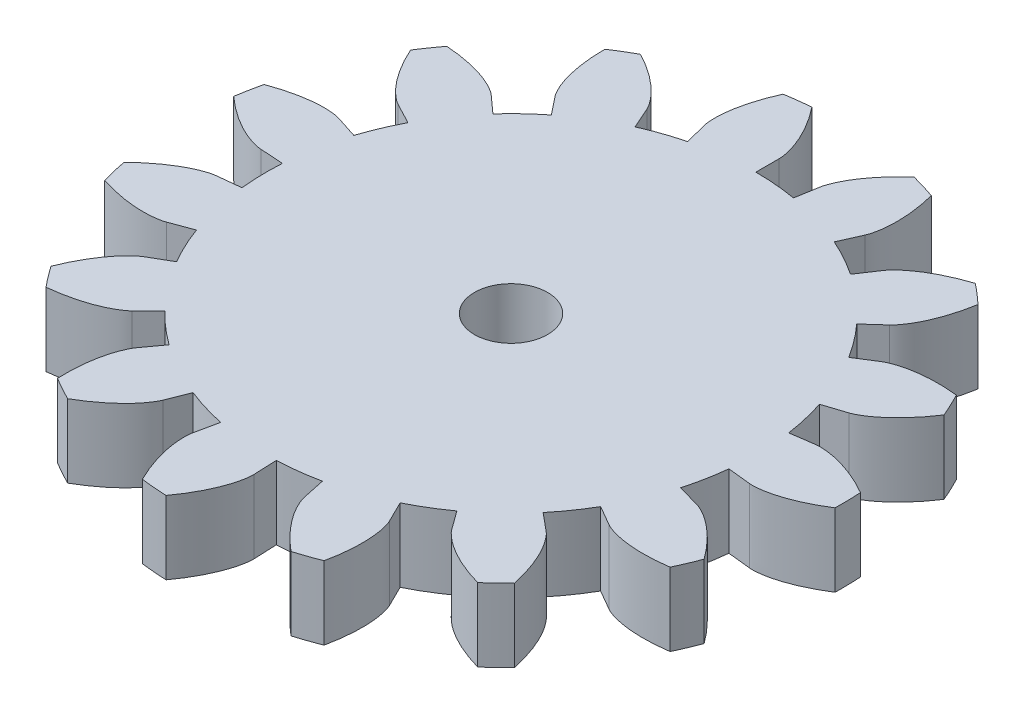
SolidWorks part; units mm, degrees
ref_plane "Front Plane" through (0, 0, 0) normal (0, 0, 1) x (1, 0, 0)
ref_plane "Top Plane" through (0, 0, 0) normal (0, 1, 0) x (1, 0, 0)
ref_plane "Right Plane" through (0, 0, 0) normal (1, 0, 0) x (0, 0, -1)
sketch "Reference attributes" plane through (0, 0, 0) normal (0, 1, 0) x (1, 0, 0)
  line L0 (0, 0) -> (15, 0) construction
  line L1 (0, -10) -> (1.56, -10) construction
  line L2 (0, 0) -> (14.4889, 3.8823) construction
  line L3 (0, 0) -> (14.0954, 5.1303) construction
  dimension "Teeth" = 15
  dimension "Module" = 1.56
  dimension "D2" = 10
  dimension "Helix Angle" = 15
  dimension "Pressure angle" = 20
sketch "Gear billet" plane through (0, 0, 0) normal (0, 1, 0) x (1, 0, 0)
  circle A0 centre (0, 0) radius 13.5525
  dimension "OuterDi" = 27.105
extrude "Gear billet Extrude" add sketch "Gear billet" along normal blind 3
ref_plane "Opposite gear face" through (0, 3, 0) normal (0, 1, 0) x (1, 0, 0)
ref_point "Twist centre point top"
ref_point "Twist centre point bottom"
ref_axis "Axis" through (0, 3, 0) along (0, -1, 0)
sketch "Involute Profile" plane through (0, 3, 0) normal (0, 1, 0) x (1, 0, 0)
  line L0 (0, 0) -> (0, 10.9944) construction
  line L1 (0, 0) -> (1.849, 10.8378) construction
  circle A0 centre (0, 0) radius 11.9925
  circle A4 centre (0, 0) radius 10.9944 construction
  spline S0 degree 4 poles (0, 10.9944) (0, 11.0283) (-0.0045, 11.1233) (-0.0311, 11.3029) (-0.0996, 11.5898) (-0.2249, 11.9512) (-0.4271, 12.399) (-0.7134, 12.8988) (-1.0767, 13.4167) (-1.516, 13.9384) (-1.9949, 14.4236) (-2.5074, 14.8731) (-3.0755, 15.3079) (-3.813, 15.7984) (-4.7381, 16.3098) (-5.863, 16.8014) (-7.1615, 17.2214) (-8.4917, 17.521) (-9.8443, 17.7042) (-11.2043, 17.778) (-12.5705, 17.7443) (-13.9226, 17.6133) (-15.2752, 17.381) (-16.4204, 17.107) (-17.4229, 16.8036) (-18.1317, 16.5596) (-18.7551, 16.3215) (-19.1642, 16.1543) (-19.7367, 15.9077) (-20.1624, 15.7055) (-20.5874, 15.5001) (-20.7978, 15.3881) (-20.9344, 15.3182) knots 0 0 0 0 0 0.005604 0.015718 0.02996 0.048734 0.068727 0.096889 0.125051 0.153212 0.181374 0.209535 0.237696 0.271429 0.327752 0.384075 0.440398 0.496721 0.553044 0.609367 0.66569 0.722013 0.778336 0.834659 0.86282 0.890982 0.909091 0.931818 0.954545 0.977273 1 1 1 1 1 construction
  spline S1 degree 4 poles (0, 10.9944) (0, 11.0283) (-0.0045, 11.1233) (-0.0311, 11.3029) (-0.0996, 11.5898) (-0.2249, 11.9512) (-0.4271, 12.399) (-0.7134, 12.8988) (-1.0767, 13.4167) (-1.516, 13.9384) (-1.9949, 14.4236) (-2.5074, 14.8731) (-3.0755, 15.3079) (-3.813, 15.7984) (-4.7381, 16.3098) (-5.863, 16.8014) (-7.1615, 17.2214) (-8.4917, 17.521) (-9.8443, 17.7042) (-11.2043, 17.778) (-12.5705, 17.7443) (-13.9226, 17.6133) (-15.2752, 17.381) (-16.4204, 17.107) (-17.4229, 16.8036) (-18.1317, 16.5596) (-18.6093, 16.3772) (-18.8455, 16.2833) (-18.9377, 16.2458) knots 0 0 0 0 0 0.005604 0.015718 0.02996 0.048734 0.068727 0.096889 0.125051 0.153212 0.181374 0.209535 0.237696 0.271429 0.327752 0.384075 0.440398 0.496721 0.553044 0.609367 0.66569 0.722013 0.778336 0.834659 0.86282 0.890982 0.909091 0.909091 0.909091 0.909091 0.909091
  spline S2 degree 4 poles (1.849, 10.8378) (1.8547, 10.8713) (1.8751, 10.9641) (1.9315, 11.1367) (2.0473, 11.408) (2.2315, 11.7431) (2.5062, 12.1506) (2.8725, 12.5951) (3.3177, 13.0446) (3.8384, 13.4849) (4.3921, 13.8827) (4.9729, 14.2396) (5.606, 14.5727) (6.4156, 14.9322) (7.4135, 15.2807) (8.6051, 15.5761) (9.9557, 15.7718) (11.3173, 15.8434) (12.6814, 15.7965) (14.0345, 15.6405) (15.3756, 15.3776) (16.6863, 15.021) (17.9807, 14.5645) (19.0634, 14.1019) (20.0006, 13.6343) (20.6584, 13.2745) (21.2328, 12.9349) (21.608, 12.7013) (22.1309, 12.362) (22.5164, 12.0911) (22.9009, 11.8171) (23.0895, 11.6713) (23.2123, 11.5794) knots 0 0 0 0 0 0.005604 0.015718 0.02996 0.048734 0.068727 0.096889 0.125051 0.153212 0.181374 0.209535 0.237696 0.271429 0.327752 0.384075 0.440398 0.496721 0.553044 0.609367 0.66569 0.722013 0.778336 0.834659 0.86282 0.890982 0.909091 0.931818 0.954545 0.977273 1 1 1 1 1 construction
  spline S3 degree 4 poles (1.849, 10.8378) (1.8547, 10.8713) (1.8751, 10.9641) (1.9315, 11.1367) (2.0473, 11.408) (2.2315, 11.7431) (2.5062, 12.1506) (2.8725, 12.5951) (3.3177, 13.0446) (3.8384, 13.4849) (4.3921, 13.8827) (4.9729, 14.2396) (5.606, 14.5727) (6.4156, 14.9322) (7.4135, 15.2807) (8.6051, 15.5761) (9.9557, 15.7718) (11.3173, 15.8434) (12.6814, 15.7965) (14.0345, 15.6405) (15.3756, 15.3776) (16.6863, 15.021) (17.9807, 14.5645) (19.0634, 14.1019) (20.0006, 13.6343) (20.6584, 13.2745) (21.0985, 13.0144) (21.3155, 12.8821) (21.4001, 12.8296) knots 0 0 0 0 0 0.005604 0.015718 0.02996 0.048734 0.068727 0.096889 0.125051 0.153212 0.181374 0.209535 0.237696 0.271429 0.327752 0.384075 0.440398 0.496721 0.553044 0.609367 0.66569 0.722013 0.778336 0.834659 0.86282 0.890982 0.909091 0.909091 0.909091 0.909091 0.909091
  point P6 (-0.2494, 11.9899)
  point P11 (2.2623, 11.7772)
  dimension "BaseDi" = 21.9888
  dimension "Adjusted Reference Diameter" = 23.985
  dimension "Reference Circumferential pitch" = 2.5117
sketch "Tooth profile" plane through (0, 3, 0) normal (0, 1, 0) x (1, 0, 0)
  line L0 (0, 0) -> (0, 10.9944) construction
  line L1 (0, 0) -> (1.849, 10.8378) construction
  line L2 (0, 0) -> (0, 10.9944)
  line L3 (0, 0) -> (1.849, 10.8378)
  line L4 (-0.2, -2.3616) -> (-0.2, 10.9944) construction
  line L5 (-0.2, -2.3616) -> (2.0461, 10.8042) construction
  circle A0 centre (0, 0) radius 13.5525 construction
  circle A1 centre (0, 0) radius 13.5525
  circle A2 centre (0, 0) radius 10.0425
  spline S0 degree 1 poles (-0.2, 10.9944) (-18.8625, 16.0605) knots 0 0 1 1 construction
  spline S1 degree 4 poles (-999.2468, 47.0982) (-31.7113, 6.7197) (-0.7279, 7.7269) (0.3375, 9.7591) (-0.0996, 11.5898) (-0.2249, 11.9512) (-0.4271, 12.399) (-0.7134, 12.8988) (-1.0767, 13.4167) (-1.516, 13.9384) (-1.9949, 14.4236) (-2.5074, 14.8731) (-3.0755, 15.3079) (-3.813, 15.7984) (-4.7381, 16.3098) (-5.863, 16.8014) (-7.1615, 17.2214) (-8.4917, 17.521) (-9.8443, 17.7042) (-11.2043, 17.778) (-12.5705, 17.7443) (-13.9226, 17.6133) (-15.2752, 17.381) (-16.4204, 17.107) (-17.4229, 16.8036) (-19.633, 16.0429) (-23.1881, 14.4164) (2.5893, 24.4855) (-944.9717, -360.906) knots -0.26224 -0.26224 -0.26224 -0.26224 -0.26224 0.005604 0.015718 0.02996 0.048734 0.068727 0.096889 0.125051 0.153212 0.181374 0.209535 0.237696 0.271429 0.327752 0.384075 0.440398 0.496721 0.553044 0.609367 0.66569 0.722013 0.778336 0.834659 0.86282 0.890982 1.186013 1.186013 1.186013 1.186013 1.186013 only from (0, 10.9944) to (-18.9377, 16.2458) construction
  spline S2 degree 4 poles (992.9358, -121.6178) (32.3898, 1.291) (2.017, 7.4944) (1.3085, 9.6768) (2.0473, 11.408) (2.2315, 11.7431) (2.5062, 12.1506) (2.8725, 12.5951) (3.3177, 13.0446) (3.8384, 13.4849) (4.3921, 13.8827) (4.9729, 14.2396) (5.606, 14.5727) (6.4156, 14.9322) (7.4135, 15.2807) (8.6051, 15.5761) (9.9557, 15.7718) (11.3173, 15.8434) (12.6814, 15.7965) (14.0345, 15.6405) (15.3756, 15.3776) (16.6863, 15.021) (17.9807, 14.5645) (19.0634, 14.1019) (20.0006, 13.6343) (22.0514, 12.5127) (25.2823, 10.3115) (1.5654, 24.5722) (870.8189, -514.6836) knots -0.26224 -0.26224 -0.26224 -0.26224 -0.26224 0.005604 0.015718 0.02996 0.048734 0.068727 0.096889 0.125051 0.153212 0.181374 0.209535 0.237696 0.271429 0.327752 0.384075 0.440398 0.496721 0.553044 0.609367 0.66569 0.722013 0.778336 0.834659 0.86282 0.890982 1.186013 1.186013 1.186013 1.186013 1.186013 only from (1.849, 10.8378) to (21.4001, 12.8296) construction
  spline S3 degree 1 poles (2.0461, 10.8042) (21.2947, 12.6596) knots 0 0 1 1 construction
  spline S4 degree 4 poles (0, 10.9944) (0, 11.0283) (-0.0045, 11.1233) (-0.0311, 11.3029) (-0.0996, 11.5898) (-0.2249, 11.9512) (-0.4271, 12.399) (-0.7134, 12.8988) (-1.0767, 13.4167) (-1.516, 13.9384) (-1.9949, 14.4236) (-2.5074, 14.8731) (-3.0755, 15.3079) (-3.813, 15.7984) (-4.7381, 16.3098) (-5.863, 16.8014) (-7.1615, 17.2214) (-8.4917, 17.521) (-9.8443, 17.7042) (-11.2043, 17.778) (-12.5705, 17.7443) (-13.9226, 17.6133) (-15.2752, 17.381) (-16.4204, 17.107) (-17.4229, 16.8036) (-18.1317, 16.5596) (-18.6093, 16.3772) (-18.8455, 16.2833) (-18.9377, 16.2458) knots 0 0 0 0 0 0.005604 0.015718 0.02996 0.048734 0.068727 0.096889 0.125051 0.153212 0.181374 0.209535 0.237696 0.271429 0.327752 0.384075 0.440398 0.496721 0.553044 0.609367 0.66569 0.722013 0.778336 0.834659 0.86282 0.890982 0.909091 0.909091 0.909091 0.909091 0.909091
  spline S5 degree 4 poles (1.849, 10.8378) (1.8547, 10.8713) (1.8751, 10.9641) (1.9315, 11.1367) (2.0473, 11.408) (2.2315, 11.7431) (2.5062, 12.1506) (2.8725, 12.5951) (3.3177, 13.0446) (3.8384, 13.4849) (4.3921, 13.8827) (4.9729, 14.2396) (5.606, 14.5727) (6.4156, 14.9322) (7.4135, 15.2807) (8.6051, 15.5761) (9.9557, 15.7718) (11.3173, 15.8434) (12.6814, 15.7965) (14.0345, 15.6405) (15.3756, 15.3776) (16.6863, 15.021) (17.9807, 14.5645) (19.0634, 14.1019) (20.0006, 13.6343) (20.6584, 13.2745) (21.0985, 13.0144) (21.3155, 12.8821) (21.4001, 12.8296) knots 0 0 0 0 0 0.005604 0.015718 0.02996 0.048734 0.068727 0.096889 0.125051 0.153212 0.181374 0.209535 0.237696 0.271429 0.327752 0.384075 0.440398 0.496721 0.553044 0.609367 0.66569 0.722013 0.778336 0.834659 0.86282 0.890982 0.909091 0.909091 0.909091 0.909091 0.909091
  spline S6 degree 3 poles (-18.8625, 16.0605) (-18.763, 16.1009) (-18.5732, 16.1761) (-18.1131, 16.3514) (-17.3753, 16.6105) (-15.8458, 17.0676) (-13.6187, 17.4947) (-10.8943, 17.6198) (-8.1871, 17.3152) (-5.5764, 16.5417) (-3.5762, 15.4725) (-2.1712, 14.3454) (-1.2532, 13.3589) (-0.6406, 12.4264) (-0.306, 11.6027) (-0.2, 11.2021) (-0.2, 10.9944) knots 0 0 0 0 0.014205 0.028409 0.056818 0.113636 0.227273 0.340909 0.454545 0.568182 0.681818 0.738636 0.795455 0.852273 0.880682 0.909091 0.909091 0.909091 0.909091 construction
  spline S7 degree 3 poles (2.0461, 10.8042) (2.081, 11.0089) (2.2529, 11.386) (2.7212, 12.1417) (3.482, 12.9579) (4.5527, 13.7759) (6.1273, 14.6507) (8.2788, 15.3683) (10.9824, 15.6918) (13.7023, 15.5368) (16.3669, 14.9552) (18.4904, 14.1597) (19.9212, 13.4519) (20.605, 13.0724) (21.029, 12.8222) (21.2035, 12.7162) (21.2947, 12.6596) knots 0 0 0 0 0.028409 0.056818 0.113636 0.170455 0.227273 0.340909 0.454545 0.568182 0.681818 0.795455 0.852273 0.880682 0.894886 0.909091 0.909091 0.909091 0.909091 construction
  dimension "RootDi" = 20.085
  dimension "Offset" = 0.2
extrude "Cut tooth profile" cut sketch "Tooth profile" against normal up to next
sketch "Tooth profile OFFSET" plane through (0, 3, 0) normal (0, 1, 0) x (1, 0, 0)
  line L4 (-0.1, -1.1808) -> (-0.1, 10.9944)
  line L5 (1.9475, 10.821) -> (-0.1, -1.1808)
  line L6 (-0.1, -1.1808) -> (-0.1, 10.9944)
  line L7 (1.9475, 10.821) -> (-0.1, -1.1808)
  circle A3 centre (0, 0) radius 13.5525 construction
  circle A4 centre (0, 0) radius 13.5525
  circle A6 centre (0, 0) radius 9.9425
  circle A7 centre (0, 0) radius 9.9425
  spline S4 degree 3 poles (1716.7359, -1048.0475) (-1.9946, 22.8241) (27.5954, 9.0093) (20.9727, 12.9716) (20.8678, 13.0334) (20.66, 13.1538) (20.5572, 13.2121) (20.3571, 13.3234) (20.2592, 13.3767) (19.7664, 13.6395) (19.3517, 13.8452) (18.5188, 14.2232) (18.1005, 14.3955) (17.2469, 14.7143) (16.8128, 14.86) (15.5017, 15.2468) (14.6091, 15.4413) (12.8042, 15.6881) (11.8918, 15.7402) (10.0722, 15.6837) (9.1646, 15.5752) (7.3899, 15.1774) (6.5221, 14.8882) (4.8834, 14.1062) (4.11, 13.6136) (3.1065, 12.7007) (2.7981, 12.3674) (2.4031, 11.8205) (2.2825, 11.6302) (2.1283, 11.3333) (2.0815, 11.2323) (-0.0855, 5.7491) (12.1344, -4.0363) (1885.5507, 682.7932) knots -1.021392 -1.021392 -1.021392 -1.021392 0.015625 0.015625 0.03125 0.03125 0.046875 0.046875 0.0625 0.0625 0.125 0.125 0.1875 0.1875 0.25 0.25 0.375 0.375 0.5 0.5 0.625 0.625 0.75 0.75 0.875 0.875 0.9375 0.9375 0.96875 0.96875 0.984375 0.984375 1.801746 1.801746 1.801746 1.801746 only from (21.3474, 12.7446) to (1.9475, 10.821)
  spline S5 degree 3 poles (-1743.85, 990.1541) (-12.6403, -1.9381) (1.0511, 5.6529) (-0.1629, 11.4224) (-0.1921, 11.5298) (-0.2941, 11.8485) (-0.381, 12.0563) (-0.6784, 12.6618) (-0.9263, 13.0422) (-1.762, 14.1109) (-2.4416, 14.7266) (-3.9255, 15.773) (-4.7322, 16.204) (-6.4147, 16.8946) (-7.2912, 17.1542) (-9.0754, 17.5159) (-9.9835, 17.618) (-11.8042, 17.6783) (-12.7168, 17.6366) (-14.0743, 17.4758) (-14.5268, 17.4052) (-15.4218, 17.2345) (-15.8631, 17.1349) (-16.7477, 16.9024) (-17.1911, 16.7694) (-17.7211, 16.5932) (-17.8266, 16.5572) (-18.0426, 16.4811) (-18.1536, 16.4408) (-18.3787, 16.3572) (-18.4925, 16.3139) (-25.6873, 13.5218) (5.8049, 22.1637) (-1868.5668, -744.4259) knots -0.801743 -0.801743 -0.801743 -0.801743 0.015625 0.015625 0.03125 0.03125 0.0625 0.0625 0.125 0.125 0.25 0.25 0.375 0.375 0.5 0.5 0.625 0.625 0.75 0.75 0.8125 0.8125 0.875 0.875 0.9375 0.9375 0.953125 0.953125 0.96875 0.96875 0.984375 0.984375 2.021397 2.021397 2.021397 2.021397 only from (-0.1, 10.9944) to (-18.9001, 16.1531)
  spline S6 degree 3 poles (21.3474, 12.7446) (21.2594, 12.7992) (21.1693, 12.854) (20.9727, 12.9716) (20.8678, 13.0334) (20.66, 13.1538) (20.5572, 13.2121) (20.3571, 13.3234) (20.2592, 13.3767) (19.7664, 13.6395) (19.3517, 13.8452) (18.5188, 14.2232) (18.1005, 14.3955) (17.2469, 14.7143) (16.8128, 14.86) (15.5017, 15.2468) (14.6091, 15.4413) (12.8042, 15.6881) (11.8918, 15.7402) (10.0722, 15.6837) (9.1646, 15.5752) (7.3899, 15.1774) (6.5221, 14.8882) (4.8834, 14.1062) (4.11, 13.6136) (3.1065, 12.7007) (2.7981, 12.3674) (2.4031, 11.8205) (2.2825, 11.6302) (2.1283, 11.3333) (2.0815, 11.2323) (2.0002, 11.0266) (1.9648, 10.9222) (1.9475, 10.821) knots 0 0 0 0 0.015625 0.015625 0.03125 0.03125 0.046875 0.046875 0.0625 0.0625 0.125 0.125 0.1875 0.1875 0.25 0.25 0.375 0.375 0.5 0.5 0.625 0.625 0.75 0.75 0.875 0.875 0.9375 0.9375 0.96875 0.96875 0.984375 0.984375 1 1 1 1
  spline S7 degree 3 poles (-0.1, 10.9944) (-0.1, 11.097) (-0.1173, 11.206) (-0.1629, 11.4224) (-0.1921, 11.5298) (-0.2941, 11.8485) (-0.381, 12.0563) (-0.6784, 12.6618) (-0.9263, 13.0422) (-1.762, 14.1109) (-2.4416, 14.7266) (-3.9255, 15.773) (-4.7322, 16.204) (-6.4147, 16.8946) (-7.2912, 17.1542) (-9.0754, 17.5159) (-9.9835, 17.618) (-11.8042, 17.6783) (-12.7168, 17.6366) (-14.0743, 17.4758) (-14.5268, 17.4052) (-15.4218, 17.2345) (-15.8631, 17.1349) (-16.7477, 16.9024) (-17.1911, 16.7694) (-17.7211, 16.5932) (-17.8266, 16.5572) (-18.0426, 16.4811) (-18.1536, 16.4408) (-18.3787, 16.3572) (-18.4925, 16.3139) (-18.7061, 16.231) (-18.8042, 16.1921) (-18.9001, 16.1531) knots 0 0 0 0 0.015625 0.015625 0.03125 0.03125 0.0625 0.0625 0.125 0.125 0.25 0.25 0.375 0.375 0.5 0.5 0.625 0.625 0.75 0.75 0.8125 0.8125 0.875 0.875 0.9375 0.9375 0.953125 0.953125 0.96875 0.96875 0.984375 0.984375 1 1 1 1
  line M3 (0, 10.0425) -> (0, 10.9944)
  spline M4 degree 4 poles (0, 10.9944) (0, 11.0283) (-0.0045, 11.1233) (-0.0311, 11.3029) (-0.0996, 11.5898) (-0.2249, 11.9512) (-0.4271, 12.399) (-0.7134, 12.8988) (-1.0767, 13.4167) (-1.516, 13.9384) (-1.9949, 14.4236) (-2.5074, 14.8731) (-3.0755, 15.3079) (-3.813, 15.7984) (-4.7381, 16.3098) (-5.863, 16.8014) (-7.1615, 17.2214) (-8.4917, 17.521) (-9.8443, 17.7042) (-11.2043, 17.778) (-12.5705, 17.7443) (-13.9226, 17.6133) (-15.2752, 17.381) (-16.4204, 17.107) (-17.4229, 16.8036) (-18.1317, 16.5596) (-18.6093, 16.3772) (-18.8455, 16.2833) (-18.9377, 16.2458) knots 0 0 0 0 0 0.005604 0.015718 0.02996 0.048734 0.068727 0.096889 0.125051 0.153212 0.181374 0.209535 0.237696 0.271429 0.327752 0.384075 0.440398 0.496721 0.553044 0.609367 0.66569 0.722013 0.778336 0.834659 0.86282 0.890982 0.909091 0.909091 0.909091 0.909091 0.909091 only from (0, 10.9944) to (-1.1598, 13.5028)
  arc M5 (-1.1598, 13.5028) -> (3.4141, 13.1154) centre (0, 0) ccw
  spline M6 degree 4 poles (21.4001, 12.8296) (21.3155, 12.8821) (21.0985, 13.0144) (20.6584, 13.2745) (20.0006, 13.6343) (19.0634, 14.1019) (17.9807, 14.5645) (16.6863, 15.021) (15.3756, 15.3776) (14.0345, 15.6405) (12.6814, 15.7965) (11.3173, 15.8434) (9.9557, 15.7718) (8.6051, 15.5761) (7.4135, 15.2807) (6.4156, 14.9322) (5.606, 14.5727) (4.9729, 14.2396) (4.3921, 13.8827) (3.8384, 13.4849) (3.3177, 13.0446) (2.8725, 12.5951) (2.5062, 12.1506) (2.2315, 11.7431) (2.0473, 11.408) (1.9315, 11.1367) (1.8751, 10.9641) (1.8547, 10.8713) (1.849, 10.8378) knots 0 0 0 0 0 0.018109 0.04627 0.074432 0.130755 0.187078 0.243401 0.299724 0.356047 0.41237 0.468693 0.525016 0.581339 0.637662 0.671395 0.699556 0.727717 0.755879 0.78404 0.812202 0.840364 0.860357 0.879131 0.893373 0.903487 0.909091 0.909091 0.909091 0.909091 0.909091 only from (3.4141, 13.1154) to (1.849, 10.8378)
  line M7 (1.849, 10.8378) -> (1.6889, 9.8995)
  arc M8 (1.6889, 9.8995) -> (0, 10.0425) centre (0, 0) ccw
  dimension "Offset" = 0.1
  dimension "D2" = 0.1
extrude "Cut Tooth profile OFFSET" [suppressed] cut sketch "Tooth profile OFFSET" against normal up to surface (10 mm away) contours S7 L6 A7 L7 S6 A4 M6 M7 M8 M3 M4 M5
sketch "Tangent meshing reference" plane through (0, 3, 0) normal (0, 1, 0) x (1, 0, 0)
  circle A0 centre (0, 0) radius 11.9925 construction
  circle A1 centre (0, 0) radius 11.9925
sketch "Gear ratio reference" plane through (0, 3, 0) normal (0, 1, 0) x (1, 0, 0)
  circle A0 centre (0, 0) radius 11.7
  dimension "Reference diameter" = 23.4
pattern_circular "Duplicate teeth" count 15 over 360 about axis through (0, 3, 0) along (0, -1, 0) of "Cut tooth profile"
other "Twist Left" [suppressed] parameters "D0"=3.84
other "Twist Right" [suppressed] parameters "D0"=3.84
mirror "Herringbone Mirror" [suppressed] about plane through (0, 3, 0) normal (0, 1, 0)
sketch "Sketch1" plane through (0, 3, 0) normal (0, 1, 0) x (1, 0, 0)
  circle A0 centre (0, 0) radius 1.5
  dimension "D1" = 3
extrude "Cut-Extrude1" cut sketch "Sketch1" against normal through all
equation "\"D1@Duplicate teeth\"=\"Teeth@Reference attributes\""
equation "\"twist\"= \"suppressed\""
equation "\"D2@Tooth profile OFFSET\"=\"Offset@Tooth profile OFFSET\""
